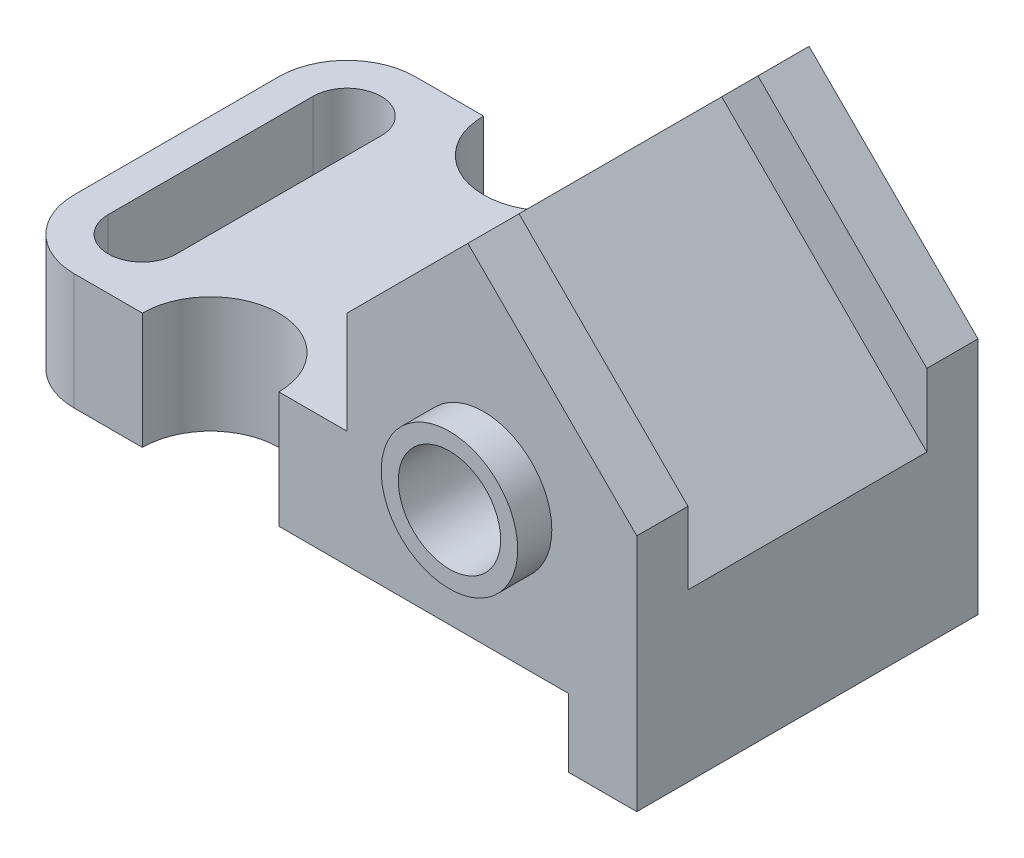
SolidWorks part; units mm, degrees
ref_plane "Спереди" through (0, 0, 0) normal (0, 0, 1) x (1, 0, 0)
ref_plane "Сверху" through (0, 0, 0) normal (0, 1, 0) x (1, 0, 0)
ref_plane "Справа" through (0, 0, 0) normal (1, 0, 0) x (0, 0, -1)
other "Configuration Table"
sketch "Эскиз1" plane through (0, 0, 0) normal (0, 0, 1) x (1, 0, 0)
  line L0 (100, 0) -> (100, 64.1)
  line L1 (0, 0) -> (184.9, 0)
  line L2 (0, 0) -> (0, 34.1)
  line L3 (0, 34.1) -> (184.9, 34.1)
  line L4 (184.9, 0) -> (184.9, 34.1)
  line L5 (184.9, 0) -> (164.9, 0)
  line L6 (184.9, 0) -> (184.9, -20)
  line L7 (184.9, -20) -> (164.9, -20)
  line L8 (164.9, 0) -> (164.9, -20)
  line L9 (184.9, 34.1) -> (184.9, 50)
  line L10 (184.9, 50) -> (135.4, 99.5)
  line L11 (135.4, 99.5) -> (100, 64.1)
  line L12 (135.4, 99.5) -> (135.4, 34.1) construction
  circle A0 centre (140, 39.1) radius 15
  dimension "D10" = 30
  dimension "D1" = 34.1
  dimension "D2" = 184.9
  dimension "D3" = 20
  dimension "D4" = 20
  dimension "D5" = 100
  dimension "D6" = 30
  dimension "D7" = 70
  dimension "D8" = 135
  dimension "D9" = 135
  dimension "D11" = 39.1
  dimension "D12" = 40
extrude "Бобышка-Вытянуть1" add sketch "Эскиз1" along normal blind 100 contours L3 L2 L1 L0 | A0 L3 L0 L1 L4 | L10 L12 A0 L3 L9 | L12 L11 L0 L3 A0 | L1 L8 L7 L6
sketch "Эскиз2" plane through (17.95, -17.95, 0) normal (-0.7071, 0.7071, 0) x (0, 0, 1)
  line L0 (100, 151.0994) -> (0, 151.0994)
  line L1 (100, 166.0994) -> (100, 116.0362) construction
  line L2 (0, 166.0994) -> (0, 116.0362) construction
  line L3 (85, 151.0994) -> (85, 166.0994)
  line L4 (100, 166.0994) -> (0, 166.0994) construction
  line L5 (15, 166.0994) -> (15, 151.0994)
  line L6 (15, 166.0994) -> (85, 166.0994)
  line L7 (15, 166.0994) -> (0, 166.0994)
  line L8 (85, 166.0994) -> (100, 166.0994)
  line L9 (100, 166.0994) -> (100, 151.0994)
  line L10 (15, 151.0994) -> (85, 151.0994)
  line M8 (100, 166.0994) -> (0, 166.0994)
  dimension "D1" = 15
  dimension "D2" = 15
  dimension "D3" = 15
extrude "Вырез-Вытянуть1" cut sketch "Эскиз2" against normal through all both and the other way through all contours L5 L0 L3 M8
sketch "Эскиз3" plane through (0, 34.1, 0) normal (0, 1, 0) x (1, 0, 0)
  line L0 (0, 0) -> (100, 0) construction
  line L1 (0, -100) -> (100, -100) construction
  line L2 (100, -100) -> (100, 0) construction
  line L3 (100, -100) -> (100, 0) construction
  circle A0 centre (60, 0) radius 20
  circle A1 centre (60, -100) radius 20
  dimension "D3" = 40
  dimension "D4" = 40
  dimension "D1" = 40
  dimension "D2" = 40
extrude "Вырез-Вытянуть2" cut sketch "Эскиз3" against normal through all both and the other way through all
sketch "Эскиз4" plane through (0, 34.1, 0) normal (0, 1, 0) x (1, 0, 0)
  line L0 (0, -50) -> (100, -50) construction
  line L1 (0, -100) -> (0, 0) construction
  line L2 (100, -100) -> (100, 0) construction
  line L3 (0, 0) -> (40, 0) construction
  line L4 (20, 0) -> (20, -100) construction
  line L5 (0, -100) -> (40, -100) construction
  line L6 (30, -20) -> (30, -80)
  line L7 (10, -20) -> (10, -80)
  circle A0 centre (20, -20) radius 10
  circle A1 centre (20, -80) radius 10
  dimension "D3" = 20
  dimension "D4" = 20
  dimension "D1" = 50
  dimension "D2" = 20
  dimension "D5" = 30
  dimension "D6" = 30
extrude "Вырез-Вытянуть3" cut sketch "Эскиз4" against normal through all both and the other way through all contours A1 L6 A0 L7 | A0 | A1
fillet "Скругление3" radius 20 2 edges at (0, 17.05, 0) (0, 17.05, 100)
sketch "Эскиз5" plane through (0, 0, 100) normal (0, 0, 1) x (1, 0, 0)
  circle A0 centre (140, 39.1) radius 20
  circle A1 centre (140, 39.1) radius 15 construction
  dimension "D1" = 40
extrude "Бобышка-Вытянуть2" add sketch "Эскиз5" along normal blind 10
sketch "Эскиз6" plane through (0, 0, 110) normal (0, 0, 1) x (1, 0, 0)
  circle A0 centre (140, 39.1) radius 15
  circle A1 centre (140, 39.1) radius 20 construction
  dimension "D1" = 30
extrude "Вырез-Вытянуть4" cut sketch "Эскиз6" against normal through all both and the other way through all
